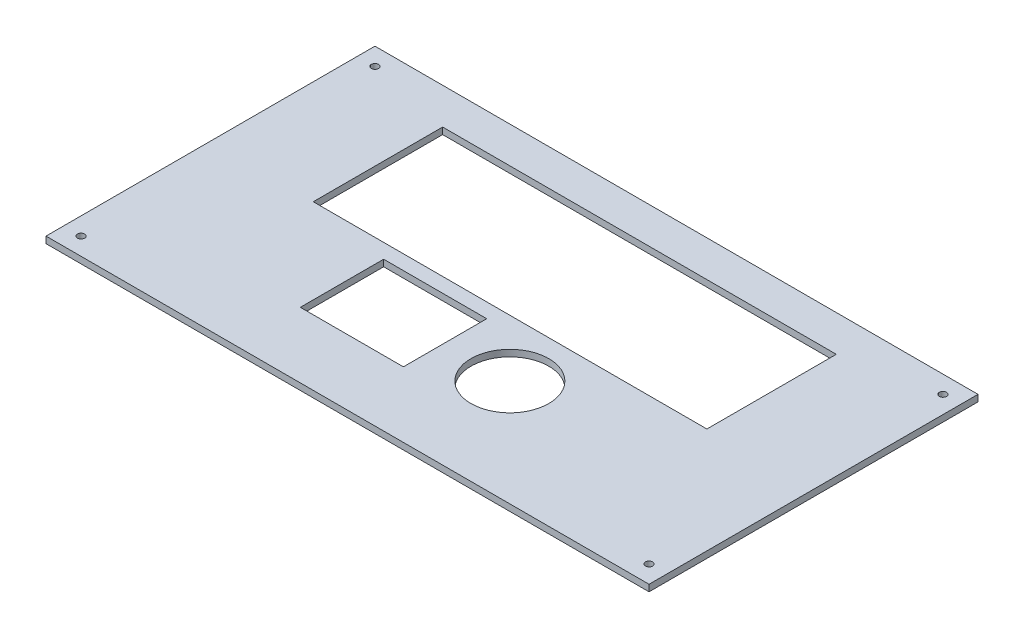
SolidWorks part; units mm, degrees
ref_plane "Ebene vorne" through (0, 0, 0) normal (0, 0, 1) x (1, 0, 0)
ref_plane "Ebene oben" through (0, 0, 0) normal (0, 1, 0) x (1, 0, 0)
ref_plane "Ebene rechts" through (0, 0, 0) normal (1, 0, 0) x (0, 0, -1)
sketch "Skizze1" plane through (0, 0, 0) normal (0, 1, 0) x (1, 0, 0)
  line L1 (-137.5, -75) -> (137.5, -75)
  line L2 (-137.5, -75) -> (-137.5, 75)
  line L3 (-137.5, 75) -> (137.5, 75)
  line L4 (137.5, -75) -> (137.5, 75)
  line L5 (-137.5, -75) -> (137.5, 75) construction
  line L6 (-137.5, 75) -> (137.5, -75) construction
  line L7 (-90.125, 58.5) -> (89.375, 58.5)
  line L8 (-90.125, 58.5) -> (-90.125, -0.5)
  line L9 (-90.125, -0.5) -> (89.375, -0.5)
  line L10 (89.375, 58.5) -> (89.375, -0.5)
  line L11 (-90.125, 58.5) -> (89.375, -0.5) construction
  line L12 (-90.125, -0.5) -> (89.375, 58.5) construction
  line L13 (-51.375, -45.15) -> (-4.375, -45.15)
  line L14 (-51.375, -45.15) -> (-51.375, -7.15)
  line L15 (-51.375, -7.15) -> (-4.375, -7.15)
  line L16 (-4.375, -45.15) -> (-4.375, -7.15)
  line L17 (-51.375, -45.15) -> (-4.375, -7.15) construction
  line L18 (-51.375, -7.15) -> (-4.375, -45.15) construction
  line L19 (-90.125, -71) -> (90.125, -71) construction
  line L20 (-90.125, -71) -> (-90.125, 29) construction
  line L21 (-90.125, 29) -> (90.125, 29) construction
  line L22 (90.125, -71) -> (90.125, 29) construction
  line L23 (-90.125, -71) -> (90.125, 29) construction
  line L24 (-90.125, 29) -> (90.125, -71) construction
  circle A0 centre (-129.5, -67) radius 1.65
  circle A1 centre (129.5, -67) radius 1.65
  circle A2 centre (-129.5, 67) radius 1.65
  circle A3 centre (129.5, 67) radius 1.65
  circle A4 centre (25.525, -26.5) radius 17.75
  point P0 (0, 0)
  point P18 (-0.375, 29)
  point P23 (-27.875, -26.15)
  point P30 (0, -21)
  dimension "D3" = 3.3
  dimension "D4" = 8
  dimension "D15" = 35.5
  dimension "D1" = 150
  dimension "D2" = 275
  dimension "D5" = 74.5
  dimension "D6" = 59
  dimension "D7" = 179.5
  dimension "D8" = 8
  dimension "D9" = 8
  dimension "D10" = 8
  dimension "D11" = 8
  dimension "D12" = 8
  dimension "D13" = 8
  dimension "D14" = 8
  dimension "D16" = 180.25
  dimension "D17" = 90.125
  dimension "D18" = 4
  dimension "D19" = 64.6
  dimension "D20" = 44.5
  dimension "D21" = 62.25
  dimension "D22" = 44.85
  dimension "D23" = 47
  dimension "D24" = 38
  dimension "D25" = 100
extrude "Aufsatz-Linear austragen1" add sketch "Skizze1" along normal blind 3
sketch "Skizze2" plane through (0, 3, 0) normal (0, 1, 0) x (1, 0, 0)
  text T0 "BMA 2020\r\nLionardo Wernli\r\nMarco Stauber\r\nBel17a"
